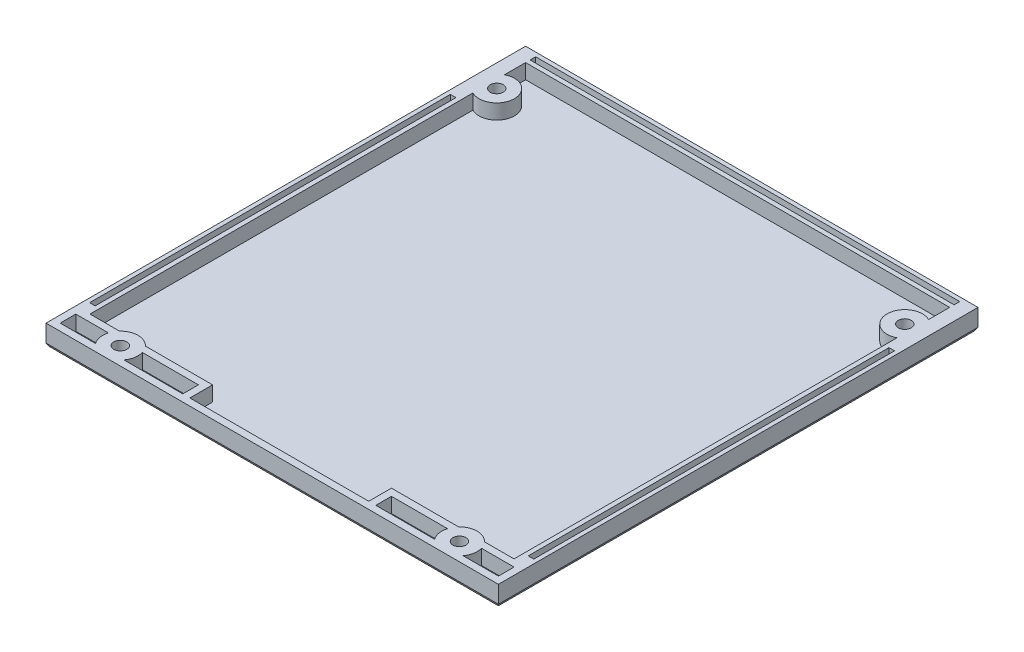
SolidWorks part; units mm, degrees
ref_plane "Спереди" through (0, 0, 0) normal (0, 0, 1) x (1, 0, 0)
ref_plane "Сверху" through (0, 0, 0) normal (0, 1, 0) x (1, 0, 0)
ref_plane "Справа" through (0, 0, 0) normal (1, 0, 0) x (0, 0, -1)
sketch "Эскиз1" plane through (0, 0, 0) normal (0, 1, 0) x (1, 0, 0)
  line L0 (0, 0) -> (0, 128.7)
  line L1 (0, 128.7) -> (121.4, 128.7)
  line L2 (121.4, 128.7) -> (121.4, 0)
  line L3 (121.4, 0) -> (0, 0)
  dimension "D1" = 128.7
  dimension "D2" = 121.4
extrude "Бобышка-Вытянуть1" add sketch "Эскиз1" along normal blind 1.5
sketch "Эскиз2" plane through (0, 1.5, 0) normal (0, 1, 0) x (1, 0, 0)
  line L0 (0, 8) -> (0, 128.7)
  line L1 (0, 128.7) -> (0, 0) construction
  line L2 (0, 128.7) -> (121.4, 128.7)
  line L3 (121.4, 128.7) -> (0, 128.7) construction
  line L4 (121.4, 128.7) -> (121.4, 8)
  line L5 (121.4, 0) -> (121.4, 128.7) construction
  line L6 (121.4, 8) -> (117.6, 8)
  line L7 (117.6, 8) -> (117.6, 124.9)
  line L8 (117.6, 124.9) -> (3.8, 124.9)
  line L9 (3.8, 124.9) -> (3.8, 8)
  line L10 (3.8, 8) -> (0, 8)
  line L11 (0, 0) -> (121.4, 0) construction
  dimension "D1" = 8
  dimension "D2" = 3.8
  dimension "D3" = 3.8
  dimension "D4" = 3.8
extrude "Бобышка-Вытянуть2" add sketch "Эскиз2" along normal blind 2
sketch "Эскиз3" plane through (0, 3.5, 0) normal (0, 1, 0) x (1, 0, 0)
  line L0 (0, 8) -> (3.8, 8)
  line L1 (3.8, 8) -> (3.8, 124.9)
  line L2 (3.8, 124.9) -> (117.6, 124.9)
  line L3 (117.6, 124.9) -> (117.6, 8)
  line L4 (117.6, 8) -> (121.4, 8)
  line L5 (121.4, 8) -> (121.4, 128.7)
  line L6 (121.4, 128.7) -> (0, 128.7)
  line L7 (0, 128.7) -> (0, 8)
  line L8 (1.1, 10.6) -> (2.6, 10.6)
  line L9 (2.6, 10.6) -> (2.6, 107.4)
  line L10 (2.6, 107.4) -> (1.1, 107.4)
  line L11 (1.1, 107.4) -> (1.1, 10.6)
  line L12 (3.8, 127.6) -> (3.8, 126.1)
  line L13 (3.8, 126.1) -> (117.6, 126.1)
  line L14 (117.6, 126.1) -> (117.6, 127.6)
  line L15 (117.6, 127.6) -> (3.8, 127.6)
  line L16 (118.8, 107.4) -> (120.3, 107.4)
  line L17 (120.3, 107.4) -> (120.3, 10.6)
  line L18 (120.3, 10.6) -> (118.8, 10.6)
  line L19 (118.8, 107.4) -> (118.8, 10.6)
  dimension "D1" = 1.1
  dimension "D2" = 1.1
  dimension "D3" = 1.1
  dimension "D4" = 1.5
  dimension "D5" = 1.5
  dimension "D6" = 1.5
  dimension "D7" = 2.6
  dimension "D8" = 21.3
  dimension "D9" = 3.8
  dimension "D10" = 3.8
  dimension "D11" = 21.3
  dimension "D12" = 2.6
extrude "Бобышка-Вытянуть3" add sketch "Эскиз3" along normal blind 2
sketch "Эскиз4" plane through (0, 5.5, 0) normal (0, 1, 0) x (1, 0, 0)
  line L0 (0, 8) -> (0, 12.75)
  line L1 (0, 128.7) -> (6, 128.7)
  line L2 (121.4, 128.7) -> (121.4, 105.2)
  line L3 (121.4, 8) -> (117.6, 8)
  line L4 (117.6, 8) -> (117.6, 12.75)
  line L5 (117.6, 124.9) -> (115.4, 124.9)
  line L6 (3.8, 124.9) -> (3.8, 105.2)
  line L7 (3.8, 8) -> (0, 8)
  line L8 (0, 12.75) -> (1.1, 12.75)
  line L9 (117.6, 12.75) -> (118.8, 12.75)
  line L10 (0, 105.2) -> (1.1, 105.2)
  line L11 (6, 128.7) -> (6, 127.6)
  line L12 (115.4, 128.7) -> (115.4, 127.6)
  line L13 (117.6, 105.2) -> (118.8, 105.2)
  line L14 (1.1, 12.75) -> (1.1, 10.6)
  line L15 (1.1, 107.4) -> (1.1, 10.6) construction
  line L16 (1.1, 10.6) -> (2.6, 10.6)
  line L17 (2.6, 10.6) -> (2.6, 12.75)
  line L18 (2.6, 10.6) -> (2.6, 107.4) construction
  line L19 (118.8, 12.75) -> (118.8, 10.6)
  line L20 (118.8, 107.4) -> (118.8, 10.6) construction
  line L21 (118.8, 10.6) -> (120.3, 10.6)
  line L22 (120.3, 10.6) -> (120.3, 12.75)
  line L23 (120.3, 10.6) -> (120.3, 107.4) construction
  line L24 (1.1, 105.2) -> (1.1, 107.4)
  line L25 (1.1, 107.4) -> (2.6, 107.4)
  line L26 (2.6, 107.4) -> (2.6, 105.2)
  line L27 (6, 127.6) -> (3.8, 127.6)
  line L28 (117.6, 127.6) -> (3.8, 127.6) construction
  line L29 (3.8, 127.6) -> (3.8, 126.1)
  line L30 (3.8, 126.1) -> (6, 126.1)
  line L31 (3.8, 126.1) -> (117.6, 126.1) construction
  line L32 (115.4, 127.6) -> (117.6, 127.6)
  line L33 (117.6, 127.6) -> (117.6, 126.1)
  line L34 (117.6, 126.1) -> (115.4, 126.1)
  line L35 (3.8, 126.1) -> (117.6, 126.1) construction
  line L36 (120.3, 105.2) -> (120.3, 107.4)
  line L37 (120.3, 10.6) -> (120.3, 107.4) construction
  line L38 (120.3, 107.4) -> (118.8, 107.4) construction
  line L39 (120.3, 107.4) -> (118.8, 107.4) construction
  line L40 (120.3, 107.4) -> (118.8, 107.4)
  line L41 (118.8, 107.4) -> (118.8, 105.2)
  line L42 (117.6, 105.2) -> (117.6, 124.9)
  line L43 (121.4, 12.75) -> (121.4, 8)
  line L44 (6, 124.9) -> (3.8, 124.9)
  line L45 (115.4, 128.7) -> (121.4, 128.7)
  line L46 (3.8, 12.75) -> (3.8, 8)
  line L47 (0, 105.2) -> (0, 128.7)
  line L48 (2.6, 12.75) -> (3.8, 12.75)
  line L49 (120.3, 12.75) -> (121.4, 12.75)
  line L50 (120.3, 105.2) -> (121.4, 105.2)
  line L51 (115.4, 126.1) -> (115.4, 124.9)
  line L52 (6, 126.1) -> (6, 124.9)
  line L53 (2.6, 105.2) -> (3.8, 105.2)
  dimension "D1" = 4.75
  dimension "D2" = 23.5
  dimension "D3" = 6
  dimension "D4" = 6
  dimension "D5" = 23.5
  dimension "D6" = 4.75
sketch "Эскиз5" plane through (0, 1.5, 0) normal (0, 1, 0) x (1, 0, 0)
  line L0 (0, 8) -> (0, 0)
  line L1 (0, 0) -> (121.4, 0)
  line L2 (121.4, 0) -> (121.4, 8)
  line L3 (121.4, 8) -> (0, 8)
  line L4 (1.9, 6.1) -> (1.9, 1.9)
  line L5 (1.9, 1.9) -> (34.8, 1.9)
  line L6 (119.5, 1.9) -> (119.5, 6.1)
  line L7 (119.5, 6.1) -> (86.6, 6.1)
  line L15 (34.8, 6.1) -> (1.9, 6.1)
  line L28 (36.7, 1.9) -> (84.7, 1.9)
  line L29 (84.7, 6.1) -> (36.7, 6.1)
  line L34 (86.6, 1.9) -> (119.5, 1.9)
  line L37 (84.7, 6.1) -> (84.7, 1.9)
  line L38 (86.6, 6.1) -> (86.6, 1.9)
  line L41 (34.8, 6.1) -> (34.8, 1.9)
  line L42 (36.7, 6.1) -> (36.7, 1.9)
  line L43 (60.7, 1.9) -> (60.7, 0) construction
  dimension "D1" = 1.9
  dimension "D2" = 1.9
  dimension "D3" = 1.9
  dimension "D4" = 1.9
  dimension "D6" = 48
  dimension "D7" = 1.9
  dimension "D21" = 1.9
extrude "Бобышка-Вытянуть5" add sketch "Эскиз5" along normal blind 4
sketch "Эскиз6" plane through (0, 0, 0) normal (0, -1, 0) x (1, 0, 0)
  line L0 (121.4, 0) -> (121.4, -128.7) construction
  line L1 (0, 0) -> (121.4, 0) construction
  line L2 (121.4, -128.7) -> (0, -128.7) construction
  line L3 (0, -128.7) -> (0, 0) construction
  line L4 (0, -128.7) -> (0, 0) construction
  circle A0 centre (106.2, -4.75) radius 3.15
  circle A1 centre (15.2, -4.75) radius 3.15
  circle A2 centre (115.45, -115) radius 3.15
  circle A3 centre (5.95, -115) radius 3.15
  dimension "D3" = 6.3
  dimension "D1" = 15.2
  dimension "D2" = 4.75
  dimension "D4" = 15.2
  dimension "D5" = 5.95
  dimension "D6" = 13.7
  dimension "D7" = 5.95
sketch "Эскиз7" plane through (0, 1.5, 0) normal (0, 1, 0) x (1, 0, 0)
  circle A0 centre (5.95, 115) radius 4.75
  circle A1 centre (115.45, 115) radius 4.75
  circle A2 centre (15.2, 4.75) radius 4.75
  circle A3 centre (106.2, 4.75) radius 4.75
  dimension "D1" = 9.5
sketch "Эскиз8" plane through (0, 0, 0) normal (0, -1, 0) x (1, 0, 0)
  circle A0 centre (15.2, -4.75) radius 1.75
  circle A1 centre (106.2, -4.75) radius 1.75
  circle A2 centre (5.95, -115) radius 1.75
  circle A3 centre (115.45, -115) radius 1.75
  circle A4 centre (106.2, -4.75) radius 3.15 construction
  circle A5 centre (5.95, -115) radius 3.15 construction
  circle A6 centre (115.45, -115) radius 3.15 construction
  circle A8 centre (15.2, -4.75) radius 3.15 construction
  dimension "D1" = 3.5
extrude "Бобышка-Вытянуть10" add sketch "Эскиз7" along normal blind 4
extrude "Вырез-Вытянуть3" cut sketch "Эскиз8" against normal blind 5.5
chamfer "Фаска1" distance 1.6 angle 45 4 edges at (106.2, 0, -6.5) (15.2, 0, -6.5) (5.95, 0, -116.75) (115.45, 0, -116.75)
sketch "Эскиз10" plane through (0, 5.5, 0) normal (0, 1, 0) x (1, 0, 0)
  line L0 (102.7359, 8) -> (18.6641, 8) construction
  line L1 (36.7, 8) -> (84.7, 8)
  line L2 (36.7, 8) -> (36.7, 1.9)
  line L3 (36.7, 1.9) -> (84.7, 1.9)
  line L4 (84.7, 8) -> (84.7, 1.9)
  line L5 (36.7, 1.9) -> (84.7, 1.9) construction
  line L6 (60.7, 1.9) -> (60.7, 0) construction
  line L7 (0, 0) -> (121.4, 0) construction
  dimension "D1" = 48
extrude "Вырез-Вытянуть4" cut sketch "Эскиз10" against normal blind 4
chamfer "Фаска2" distance 0.5 angle 60 4 edges at (121.4, 0, -64.35) (60.7, 0, 0) (60.7, 0, -128.7) (0, 0, -64.35)
